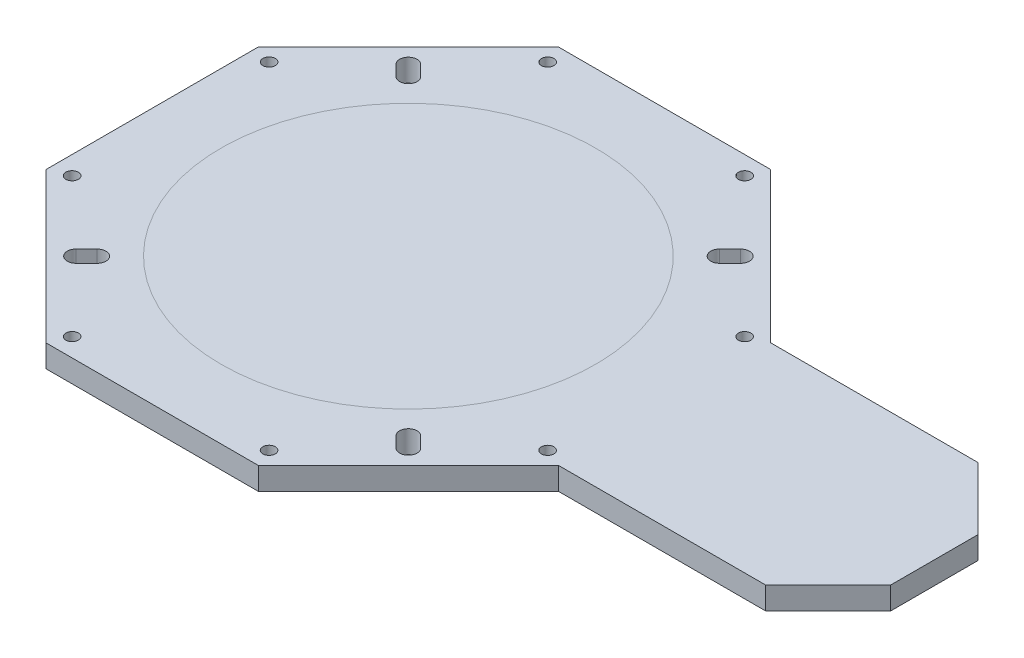
SolidWorks part; units mm, degrees
ref_plane "Front Plane" through (0, 0, 0) normal (0, 0, 1) x (1, 0, 0)
ref_plane "Top Plane" through (0, 0, 0) normal (0, 1, 0) x (1, 0, 0)
ref_plane "Right Plane" through (0, 0, 0) normal (1, 0, 0) x (0, 0, -1)
sketch "Sketch1" plane through (0, 0, 0) normal (0, 1, 0) x (1, 0, 0)
  line L0 (-42.5, 102.6041) -> (-102.6041, 42.5)
  line L5 (185.6041, 42.5) -> (210.6041, 17.5)
  line L6 (102.6041, 42.5) -> (185.6041, 42.5)
  line L7 (-102.6041, -42.5) -> (-42.5, -102.6041)
  line L8 (-42.5, -102.6041) -> (42.5, -102.6041)
  line L9 (42.5, -102.6041) -> (102.6041, -42.5)
  line L10 (102.6041, -42.5) -> (102.6041, 42.5)
  line L11 (102.6041, 42.5) -> (42.5, 102.6041)
  line L12 (42.5, 102.6041) -> (-42.5, 102.6041)
  line L13 (-102.6041, 42.5) -> (-102.6041, -42.5)
  line L14 (102.6041, 42.5) -> (102.6041, -42.5)
  line L15 (102.6041, -42.5) -> (185.6041, -42.5)
  line L16 (210.6041, 17.5) -> (210.6041, -17.5)
  line L17 (185.6041, -42.5) -> (210.6041, -17.5)
  line L18 (0, 102.6041) -> (0, -102.6041) construction
  line L19 (-102.6041, 0) -> (102.6041, 0) construction
  line L20 (72.552, 72.552) -> (-72.552, -72.552) construction
  line L21 (-72.552, 72.552) -> (72.552, -72.552) construction
  line L22 (-69.0165, 64.0668) -> (-64.7739, 59.8241)
  line L23 (-69.0165, 64.0668) -> (-64.0668, 69.0165)
  line L24 (-64.7739, 59.8241) -> (-59.8241, 64.7739)
  line L25 (-64.0668, 69.0165) -> (-59.8241, 64.7739)
  line L26 (64.0668, 69.0165) -> (59.8241, 64.7739)
  line L27 (64.0668, 69.0165) -> (69.0165, 64.0668)
  line L28 (69.0165, 64.0668) -> (64.7739, 59.8241)
  line L29 (59.8241, 64.7739) -> (64.7739, 59.8241)
  line L30 (69.0165, -64.0668) -> (64.7739, -59.8241)
  line L31 (69.0165, -64.0668) -> (64.0668, -69.0165)
  line L32 (64.0668, -69.0165) -> (59.8241, -64.7739)
  line L33 (64.7739, -59.8241) -> (59.8241, -64.7739)
  line L34 (-64.0668, -69.0165) -> (-59.8241, -64.7739)
  line L35 (-64.0668, -69.0165) -> (-69.0165, -64.0668)
  line L36 (-69.0165, -64.0668) -> (-64.7739, -59.8241)
  line L37 (-59.8241, -64.7739) -> (-64.7739, -59.8241)
  circle A0 centre (0, 0) radius 102.6041 construction
  circle A1 centre (-95.2171, -39.4288) radius 2.5
  circle A2 centre (-95.209, 39.4483) radius 2.5
  circle A3 centre (-39.4288, 95.2171) radius 2.5
  circle A4 centre (39.4483, 95.209) radius 2.5
  circle A5 centre (95.2171, 39.4288) radius 2.5
  circle A6 centre (95.209, -39.4483) radius 2.5
  circle A7 centre (39.4288, -95.2171) radius 2.5
  circle A8 centre (-39.4483, -95.209) radius 2.5
  circle A9 centre (-66.5416, 66.5416) radius 3.5
  circle A10 centre (-62.299, 62.299) radius 3.5
  circle A11 centre (66.5416, 66.5416) radius 3.5
  circle A12 centre (62.299, 62.299) radius 3.5
  circle A13 centre (66.5416, -66.5416) radius 3.5
  circle A14 centre (62.299, -62.299) radius 3.5
  circle A15 centre (-66.5416, -66.5416) radius 3.5
  circle A16 centre (-62.299, -62.299) radius 3.5
  point P0 (0, 0)
  point P3 (210.6041, -42.5)
  point P4 (210.6041, 42.5)
  point P37 (0, 0)
  point P78 (0, 0)
  dimension "D3" = 5
  dimension "D9" = 7
  dimension "D10" = 5
  dimension "D11" = 7
  dimension "D12" = 13
  dimension "D1" = 85
  dimension "D2" = 108
  dimension "D4" = 8
  dimension "D7" = 7.387
  dimension "D8" = 8
  dimension "D13" = 360
  dimension "D14" = 3.5
  dimension "D15" = 4
extrude "Boss-Extrude1" add sketch "Sketch1" along normal blind 9 contours L0 L13 L7 L8 L9 L10 L11 L12 A16 L34 A15 L36 A14 L30 A13 L32 A12 L26 A11 L28 A10 L22 A9 L25 A8 A7 A6 A5 A4 A3 A2 A1 | L15 L17 L16 L5 L6 L10
ref_plane "Plane1" through (-42.5, 9, -102.6041) normal (-1, 0, 0) x (0, 0, 1)
sketch "Sketch2" plane through (0, 9, 0) normal (0, 1, 0) x (1, 0, 0)
  circle A0 centre (0, 0) radius 75
  dimension "D1" = 150
split line "Split Line1"
